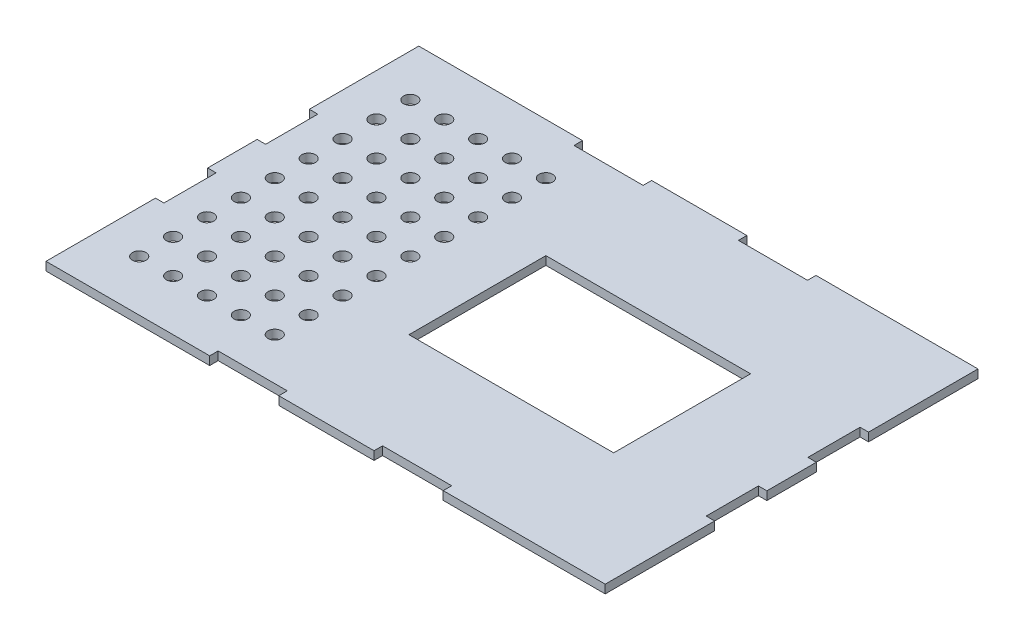
SolidWorks part; units mm, degrees
ref_plane "Front Plane" through (0, 0, 0) normal (0, 0, 1) x (1, 0, 0)
ref_plane "Top Plane" through (0, 0, 0) normal (0, 1, 0) x (1, 0, 0)
ref_plane "Right Plane" through (0, 0, 0) normal (1, 0, 0) x (0, 0, -1)
sketch "Sketch1" plane through (0, 0, 0) normal (0, 1, 0) x (1, 0, 0)
  line L1 (-101.6, -66.675) -> (101.6, -66.675)
  line L2 (-101.6, -66.675) -> (-101.6, 66.675)
  line L3 (-101.6, 66.675) -> (101.6, 66.675)
  line L4 (101.6, -66.675) -> (101.6, 66.675)
  line L5 (-101.6, -66.675) -> (101.6, 66.675) construction
  line L6 (-101.6, 66.675) -> (101.6, -66.675) construction
  point P0 (0, 0)
  dimension "D1" = 203.2
  dimension "D2" = 133.35
extrude "Boss-Extrude1" add sketch "Sketch1" along normal blind 3.175
sketch "Sketch2" plane through (0, 3.175, 0) normal (0, 1, 0) x (1, 0, 0)
  circle A0 centre (-88.9, 50.8) radius 2.54
  circle A1 centre (-76.2, 50.8) radius 2.54
  circle A2 centre (-63.5, 50.8) radius 2.54
  circle A3 centre (-50.8, 50.8) radius 2.54
  circle A4 centre (-76.2, 38.1) radius 2.54
  circle A5 centre (-63.5, 38.1) radius 2.54
  circle A6 centre (-50.8, 38.1) radius 2.54
  circle A7 centre (-76.2, 25.4) radius 2.54
  circle A8 centre (-63.5, 25.4) radius 2.54
  circle A9 centre (-50.8, 25.4) radius 2.54
  circle A10 centre (-76.2, 12.7) radius 2.54
  circle A11 centre (-63.5, 12.7) radius 2.54
  circle A12 centre (-50.8, 12.7) radius 2.54
  circle A13 centre (-76.2, 0) radius 2.54
  circle A14 centre (-63.5, 0) radius 2.54
  circle A15 centre (-50.8, 0) radius 2.54
  circle A16 centre (-76.2, -12.7) radius 2.54
  circle A17 centre (-63.5, -12.7) radius 2.54
  circle A18 centre (-50.8, -12.7) radius 2.54
  circle A19 centre (-76.2, -25.4) radius 2.54
  circle A20 centre (-63.5, -25.4) radius 2.54
  circle A21 centre (-50.8, -25.4) radius 2.54
  circle A22 centre (-76.2, -38.1) radius 2.54
  circle A23 centre (-63.5, -38.1) radius 2.54
  circle A24 centre (-50.8, -38.1) radius 2.54
  circle A25 centre (-76.2, -50.8) radius 2.54
  circle A26 centre (-63.5, -50.8) radius 2.54
  circle A27 centre (-50.8, -50.8) radius 2.54
  circle A28 centre (-88.9, 38.1) radius 2.54
  circle A29 centre (-88.9, 25.4) radius 2.54
  circle A30 centre (-88.9, 12.7) radius 2.54
  circle A31 centre (-88.9, 0) radius 2.54
  circle A32 centre (-88.9, -12.7) radius 2.54
  circle A33 centre (-88.9, -25.4) radius 2.54
  circle A34 centre (-88.9, -38.1) radius 2.54
  circle A35 centre (-88.9, -50.8) radius 2.54
  circle A36 centre (-38.1, 50.8) radius 2.54
  circle A37 centre (-38.1, 38.1) radius 2.54
  circle A38 centre (-38.1, 25.4) radius 2.54
  circle A39 centre (-38.1, 12.7) radius 2.54
  circle A40 centre (-38.1, 0) radius 2.54
  circle A41 centre (-38.1, -12.7) radius 2.54
  circle A42 centre (-38.1, -25.4) radius 2.54
  circle A43 centre (-38.1, -38.1) radius 2.54
  circle A44 centre (-38.1, -50.8) radius 2.54
  dimension "D1" = 5.08
  dimension "D2" = 88.9
  dimension "D3" = 50.8
  dimension "D4" = 5
  dimension "D5" = 9
extrude "Cut-Extrude1" cut sketch "Sketch2" against normal through all
sketch "Sketch3" plane through (0, 3.175, 0) normal (0, 1, 0) x (1, 0, 0)
  line L0 (101.6, 66.675) -> (-101.6, 66.675) construction
  line L1 (-79.121, 66.675) -> (-43.434, 66.675)
  line L2 (-79.121, 66.675) -> (-79.121, 69.85)
  line L3 (-79.121, 69.85) -> (-43.434, 69.85)
  line L4 (-43.434, 66.675) -> (-43.434, 69.85)
  line L5 (-101.6, 66.675) -> (-101.6, -66.675) construction
  line L6 (-17.526, 66.675) -> (18.161, 66.675)
  line L7 (18.161, 66.675) -> (18.161, 69.85)
  line L8 (-17.526, 69.85) -> (18.161, 69.85)
  line L9 (-17.526, 66.675) -> (-17.526, 69.85)
  line L10 (44.069, 66.675) -> (79.756, 66.675)
  line L11 (79.756, 66.675) -> (79.756, 69.85)
  line L12 (44.069, 69.85) -> (79.756, 69.85)
  line L13 (44.069, 66.675) -> (44.069, 69.85)
  line L14 (0, 0) -> (101.6, 0) construction
  line L15 (101.6, -66.675) -> (101.6, 66.675) construction
  line L16 (44.069, -66.675) -> (44.069, -69.85)
  line L17 (44.069, -69.85) -> (79.756, -69.85)
  line L18 (79.756, -66.675) -> (79.756, -69.85)
  line L19 (44.069, -66.675) -> (79.756, -66.675)
  line L20 (-17.526, -66.675) -> (-17.526, -69.85)
  line L21 (-17.526, -69.85) -> (18.161, -69.85)
  line L22 (18.161, -66.675) -> (18.161, -69.85)
  line L23 (-17.526, -66.675) -> (18.161, -66.675)
  line L24 (-43.434, -66.675) -> (-43.434, -69.85)
  line L25 (-79.121, -69.85) -> (-43.434, -69.85)
  line L26 (-79.121, -66.675) -> (-79.121, -69.85)
  line L27 (-79.121, -66.675) -> (-43.434, -66.675)
  point P6 (-61.2775, 66.675)
  dimension "D1" = 3.175
  dimension "D2" = 40.3225
  dimension "D3" = 22.479
  dimension "D4" = 35.687
  dimension "D5" = 3
extrude "Boss-Extrude2" add sketch "Sketch3" against normal blind 3.175
sketch "Sketch4" plane through (0, 3.175, 0) normal (0, 1, 0) x (1, 0, 0)
  line L0 (-101.6, 66.675) -> (-101.6, -66.675) construction
  line L1 (-101.6, 47.371) -> (-104.775, 47.371)
  line L2 (-101.6, 47.371) -> (-101.6, 28.829)
  line L3 (-101.6, 28.829) -> (-104.775, 28.829)
  line L4 (-104.775, 47.371) -> (-104.775, 28.829)
  line L5 (-104.775, 9.271) -> (-104.775, -9.271)
  line L6 (-79.121, 66.675) -> (-101.6, 66.675) construction
  line L7 (-101.6, -9.271) -> (-104.775, -9.271)
  line L8 (-101.6, 9.271) -> (-101.6, -9.271)
  line L9 (-101.6, 9.271) -> (-104.775, 9.271)
  line L10 (-104.775, -28.829) -> (-104.775, -47.371)
  line L11 (-101.6, -47.371) -> (-104.775, -47.371)
  line L12 (-101.6, -28.829) -> (-101.6, -47.371)
  line L13 (-101.6, -28.829) -> (-104.775, -28.829)
  line L14 (0, 0) -> (0, 30.8846) construction
  line L15 (101.6, -28.829) -> (104.775, -28.829)
  line L16 (101.6, -28.829) -> (101.6, -47.371)
  line L17 (101.6, -47.371) -> (104.775, -47.371)
  line L18 (104.775, -28.829) -> (104.775, -47.371)
  line L19 (101.6, 9.271) -> (104.775, 9.271)
  line L20 (101.6, 9.271) -> (101.6, -9.271)
  line L21 (101.6, -9.271) -> (104.775, -9.271)
  line L22 (104.775, 9.271) -> (104.775, -9.271)
  line L23 (104.775, 47.371) -> (104.775, 28.829)
  line L24 (101.6, 28.829) -> (104.775, 28.829)
  line L25 (101.6, 47.371) -> (101.6, 28.829)
  line L26 (101.6, 47.371) -> (104.775, 47.371)
  point P9 (-101.6, 38.1)
  point P10 (-103.1875, 47.371)
  dimension "D1" = 3.175
  dimension "D2" = 28.575
  dimension "D3" = 18.542
  dimension "D4" = 19.304
  dimension "D6" = 38.1
  dimension "D5" = 3
extrude "Boss-Extrude3" add sketch "Sketch4" against normal blind 3.175
sketch "Sketch5" plane through (0, 3.175, 0) normal (0, 1, 0) x (1, 0, 0)
  line L0 (-104.775, -47.371) -> (-104.775, -69.85)
  line L1 (-104.775, -69.85) -> (-79.121, -69.85)
  line L2 (-79.121, -69.85) -> (-79.121, -66.675)
  line L3 (-79.121, -66.675) -> (-101.6, -66.675)
  line L4 (-101.6, -66.675) -> (-101.6, -47.371)
  line L5 (-101.6, -47.371) -> (-104.775, -47.371)
  line L6 (0, 0) -> (0, -32.8131) construction
  line L7 (0, 0) -> (43.4933, 0) construction
  line L8 (-101.6, 47.371) -> (-104.775, 47.371)
  line L9 (-101.6, 66.675) -> (-101.6, 47.371)
  line L10 (-79.121, 66.675) -> (-101.6, 66.675)
  line L11 (-79.121, 69.85) -> (-79.121, 66.675)
  line L12 (-104.775, 69.85) -> (-79.121, 69.85)
  line L13 (-104.775, 47.371) -> (-104.775, 69.85)
  line L14 (104.775, 47.371) -> (104.775, 69.85)
  line L15 (104.775, 69.85) -> (79.121, 69.85)
  line L16 (79.121, 69.85) -> (79.121, 66.675)
  line L17 (79.121, 66.675) -> (101.6, 66.675)
  line L18 (101.6, 66.675) -> (101.6, 47.371)
  line L19 (101.6, 47.371) -> (104.775, 47.371)
  line L20 (101.6, -47.371) -> (104.775, -47.371)
  line L21 (101.6, -66.675) -> (101.6, -47.371)
  line L22 (79.121, -66.675) -> (101.6, -66.675)
  line L23 (79.121, -69.85) -> (79.121, -66.675)
  line L24 (104.775, -69.85) -> (79.121, -69.85)
  line L25 (104.775, -47.371) -> (104.775, -69.85)
extrude "Boss-Extrude4" add sketch "Sketch5" against normal blind 3.175
sketch "Sketch6" plane through (0, 3.175, 0) normal (0, 1, 0) x (1, 0, 0)
  line L0 (101.6, 9.271) -> (101.6, 28.829) construction
  line L1 (63.754, 25.654) -> (-12.954, 25.654)
  line L2 (63.754, 25.654) -> (63.754, -25.654)
  line L3 (63.754, -25.654) -> (-12.954, -25.654)
  line L4 (-12.954, 25.654) -> (-12.954, -25.654)
  line L5 (63.754, 25.654) -> (-12.954, -25.654) construction
  line L6 (63.754, -25.654) -> (-12.954, 25.654) construction
  point P0 (25.4, 0)
  dimension "D1" = 51.308
  dimension "D2" = 76.708
  dimension "D3" = 76.2
extrude "Cut-Extrude2" cut sketch "Sketch6" against normal through all
